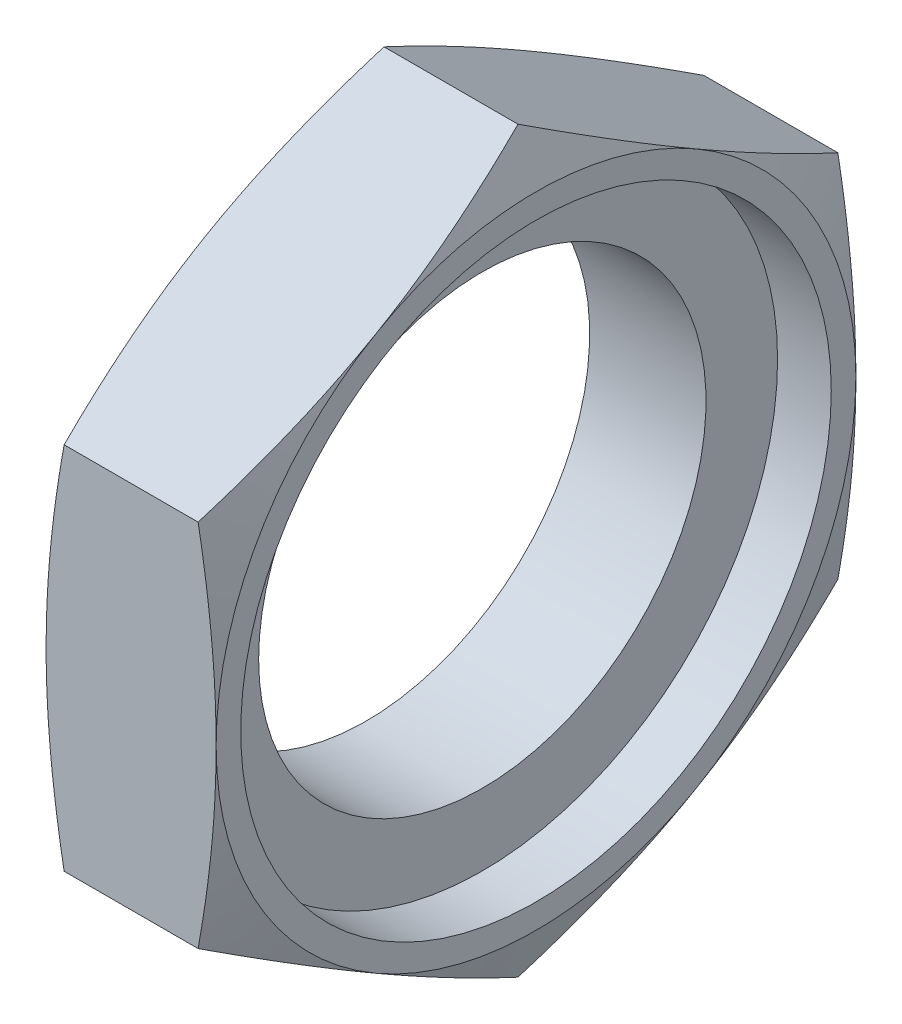
SolidWorks part; units mm, degrees
material "AISI 1020"
ref_plane "Plano superior" through (0, 0, 0) normal (0, 0, 1) x (1, 0, 0)
ref_plane "Plano frontal" through (0, 0, 0) normal (0, 1, 0) x (1, 0, 0)
ref_plane "Plano direito" through (0, 0, 0) normal (1, 0, 0) x (0, 0, -1)
sketch "Esboço1" plane through (0, 0, 0) normal (1, 0, 0) x (0, 0, -1)
  line L1 (14.3, 8.2561) -> (0, 16.5122)
  line L2 (0, 16.5122) -> (-14.3, 8.2561)
  line L3 (-14.3, 8.2561) -> (-14.3, -8.2561)
  line L4 (-14.3, -8.2561) -> (0, -16.5122)
  line L5 (0, -16.5122) -> (14.3, -8.2561)
  line L6 (14.3, -8.2561) -> (14.3, 8.2561)
  circle A0 centre (0, 0) radius 14.3 construction
  circle A1 centre (0, 0) radius 10
  dimension "D1" = 28.6
  dimension "D2" = 20
extrude "Ressalto-extrusão1" add sketch "Esboço1" along normal blind 7.6
cosmetic thread "Representação de rosca2" parameters "D2"=22
sketch "Esboço9" plane through (0, 0, 0) normal (-1, 0, 0) x (0, 0, 1)
  circle A0 centre (0, 0) radius 14.3
extrude "Corte-extrusão3" cut sketch "Esboço9" against normal blind 10 draft 75 flip side to cut
sketch "Esboço10" plane through (7.6, 0, 0) normal (1, 0, 0) x (0, 0, -1)
  circle A0 centre (0, 0) radius 14.3
extrude "Corte-extrusão5" cut sketch "Esboço10" against normal blind 15 draft 75 flip side to cut
sketch "Esboço3" plane through (0, 0, 0) normal (-1, 0, 0) x (0, 0, 1)
  circle A0 centre (0, 0) radius 14.3
sketch "Esboço4" plane through (7.6, 0, 0) normal (1, 0, 0) x (0, 0, -1)
  circle A0 centre (0, 0) radius 14.3
hole_wizard "Furo1" positions "Esboço5" profile "Esboço6" legacy
sketch "Esboço5" plane through (7.6, 0, 0) normal (1, 0, 0) x (0, 0, -1)
  point P0 (0, 0)
  point P3 (0, 0)
sketch "Esboço6" plane through (7.6, 0, 0) normal (0, 1, 0) x (0, 0, -1)
  line L0 (0, 0) -> (0, 2.4)
  line L1 (0, 2.4) -> (13.2, 2.4)
  line L2 (13.2, 2.4) -> (13.2, 0)
  line L3 (13.2, 0) -> (0, 0)
  line L4 (0, 110) -> (0, -10) construction
  dimension "Diameter" = 26.4
  dimension "Depth" = 2.4
sketch "Esboço7" plane through (7.6, 0, 0) normal (1, 0, 0) x (0, 0, -1)
  circle A0 centre (0, 0) radius 14.3
extrude "Corte-extrusão1" cut sketch "Esboço7" against normal blind 13 draft 70 flip side to cut
sketch "Esboço8" plane through (0, 0, 0) normal (-1, 0, 0) x (0, 0, 1)
  circle A0 centre (0, 0) radius 14.3
extrude "Corte-extrusão2" cut sketch "Esboço8" against normal blind 13 draft 70 flip side to cut
